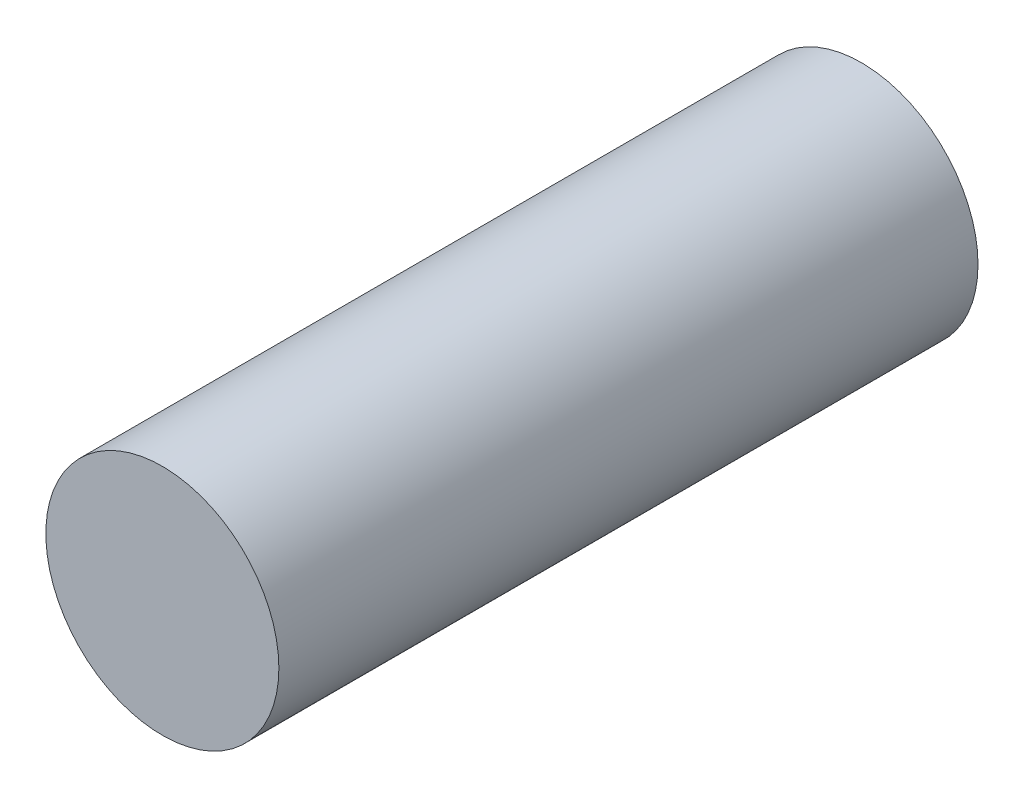
SolidWorks part; units mm, degrees
ref_plane "前视基准面" through (0, 0, 0) normal (0, 0, 1) x (1, 0, 0)
ref_plane "上视基准面" through (0, 0, 0) normal (0, 1, 0) x (1, 0, 0)
ref_plane "右视基准面" through (0, 0, 0) normal (1, 0, 0) x (0, 0, -1)
other "Configuration Table"
sketch "草图1" plane through (0, 0, 0) normal (0, 0, 1) x (1, 0, 0)
  circle A3 centre (0, 0) radius 5
  dimension "D2" = 10
extrude "凸台-拉伸1" add sketch "草图1" along normal mid plane 30
